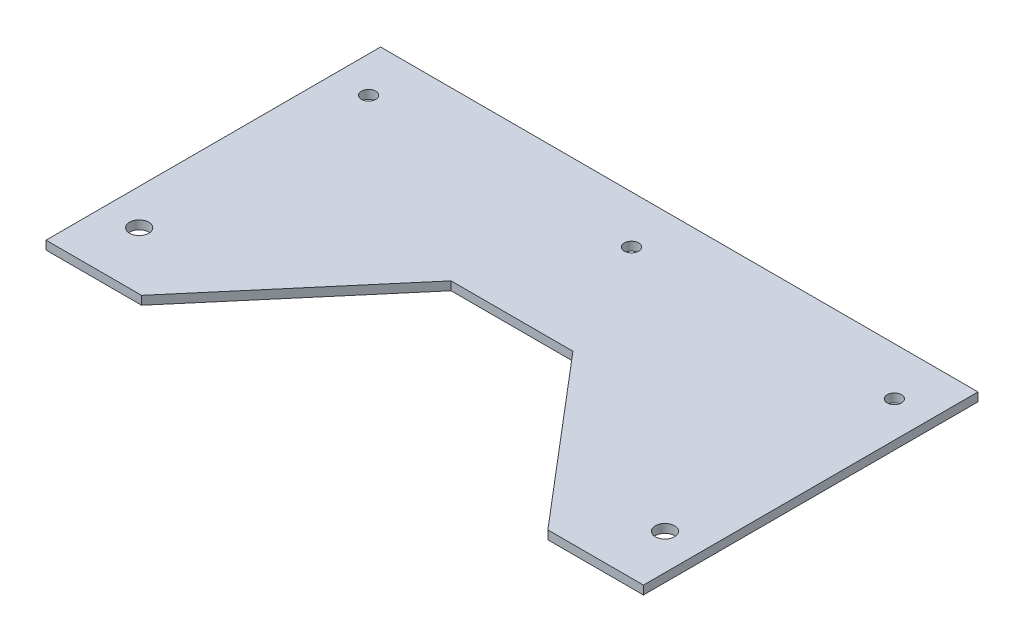
SolidWorks part; units mm, degrees
material "6061-T6 (SS)"
ref_plane "Front Plane" through (0, 0, 0) normal (0, 0, 1) x (1, 0, 0)
ref_plane "Top Plane" through (0, 0, 0) normal (0, 1, 0) x (1, 0, 0)
ref_plane "Right Plane" through (0, 0, 0) normal (1, 0, 0) x (0, 0, -1)
sketch "Sketch1" plane through (0, 0, 0) normal (0, 1, 0) x (1, 0, 0)
  line L0 (-45.966, 39.7018) -> (33.409, 39.7018)
  line L1 (33.409, 39.7018) -> (33.409, -49.1982)
  line L2 (33.409, -49.1982) -> (8.009, -49.1982)
  line L3 (8.009, -49.1982) -> (-45.966, 14.3018)
  line L4 (-45.966, 14.3018) -> (-45.966, 39.7018)
  line L5 (-71.366, 39.7018) -> (8.009, 39.7018)
  line L6 (-96.766, 39.7018) -> (-17.391, 39.7018)
  circle A0 centre (23.884, -33.9582) radius 2.5527
  circle A1 centre (23.884, 27.0018) radius 1.905
  dimension "D5" = 5.1054
  dimension "D6" = 3.81
  dimension "D9" = 90
  dimension "D1" = 25.4
  dimension "D2" = 25.4
  dimension "D3" = 79.375
  dimension "D4" = 88.9
  dimension "D7" = 9.525
  dimension "D8" = 9.525
  dimension "D10" = 12.7
  dimension "D11" = 60.96
  dimension "D12" = 90
  dimension "D13" = 90
extrude "Boss-Extrude1" add sketch "Sketch1" along normal mid plane 2.286
mirror "Mirror1" about plane through (-45.966, 1.143, 0) normal (-1, 0, 0) of "Boss-Extrude1"
sketch "Sketch3" plane through (0, 1.143, 0) normal (0, 1, 0) x (1, 0, 0)
  line L0 (-125.341, 39.7018) -> (33.409, 39.7018) construction
  circle A0 centre (-45.966, 27.0018) radius 1.905
  circle A1 centre (23.884, 27.0018) radius 1.905 construction
  dimension "D1" = 3.81
  dimension "D2" = 69.85
  dimension "D3" = 12.7
extrude "Cut-Extrude1" cut sketch "Sketch3" against normal through all
sketch "Sketch4" plane through (0, 1.143, 0) normal (0, 1, 0) x (1, 0, 0)
  line L0 (-125.341, 39.7018) -> (33.409, 39.7018) construction
  line L1 (-71.366, 14.3018) -> (-20.566, 14.3018)
  line L2 (-71.366, 14.3018) -> (-71.366, -4.7482)
  line L3 (-71.366, -4.7482) -> (-20.566, -4.7482)
  line L4 (-20.566, 14.3018) -> (-20.566, -4.7482)
  circle A0 centre (-45.966, 27.0018) radius 1.905 construction
  dimension "D1" = 50.8
  dimension "D2" = 25.4
  dimension "D3" = 25.4
  dimension "D4" = 19.05
extrude "Boss-Extrude2" add sketch "Sketch4" against normal blind 2.286
